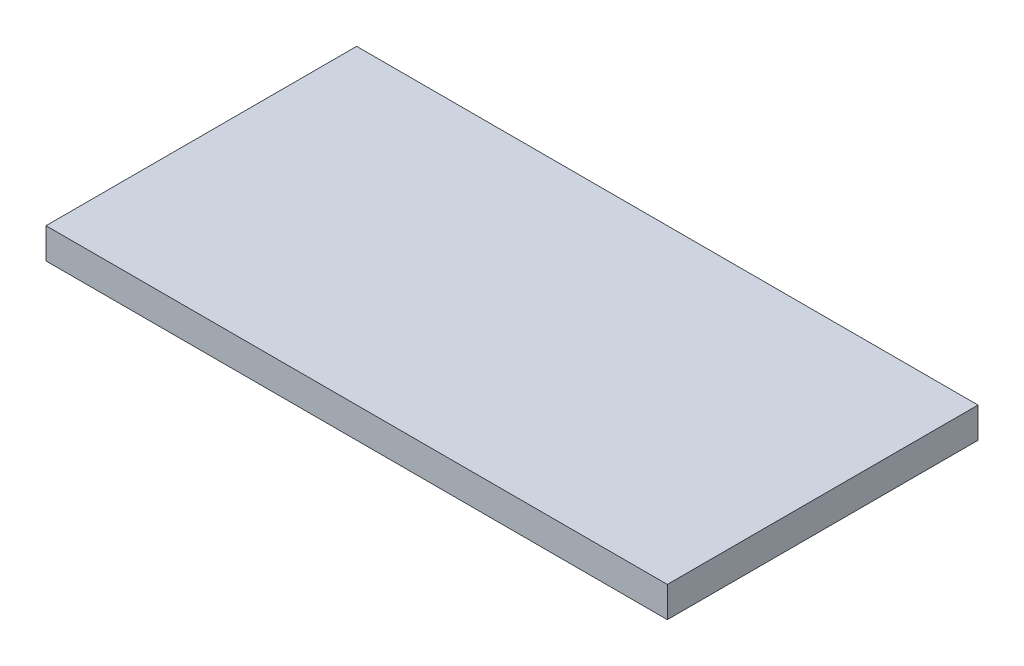
SolidWorks part; units mm, degrees
ref_plane "Front Plane" through (0, 0, 0) normal (0, 0, 1) x (1, 0, 0)
ref_plane "Top Plane" through (0, 0, 0) normal (0, 1, 0) x (1, 0, 0)
ref_plane "Right Plane" through (0, 0, 0) normal (1, 0, 0) x (0, 0, -1)
sketch "Sketch1" plane through (0, 0, 0) normal (0, 1, 0) x (1, 0, 0)
  line L0 (-609.6, 304.8) -> (609.6, -304.8) construction
  line L1 (-609.6, 304.8) -> (609.6, 304.8)
  line L2 (-609.6, 304.8) -> (-609.6, -304.8)
  line L3 (-609.6, -304.8) -> (609.6, -304.8)
  line L4 (609.6, 304.8) -> (609.6, -304.8)
  line L5 (-609.6, -304.8) -> (609.6, 304.8) construction
  point P4 (0, 0)
  dimension "D1" = 1219.2
  dimension "D2" = 609.6
extrude "Extrude1" add sketch "Sketch1" along normal blind 59.944
